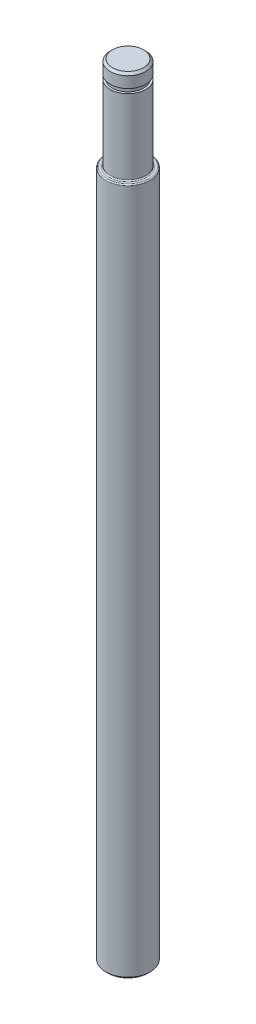
SolidWorks part; units mm, degrees
material "AISI 1045 Aço, trefilado"
ref_plane "Plano frontal" through (0, 0, 0) normal (0, 0, 1) x (1, 0, 0)
ref_plane "Plano superior" through (0, 0, 0) normal (0, 1, 0) x (1, 0, 0)
ref_plane "Plano direito" through (0, 0, 0) normal (1, 0, 0) x (0, 0, -1)
sketch "Esboço1" plane through (0, 0, 0) normal (0, 1, 0) x (1, 0, 0)
  circle A0 centre (0, 0) radius 5
extrude "Ressalto-extrusão1" add sketch "Esboço1" along normal blind 94 and the other way blind 82
sketch "Esboço2" plane through (0, 94, 0) normal (0, 1, 0) x (1, 0, 0)
  circle A0 centre (0, 0) radius 4
  circle A1 centre (0, 0) radius 14
  dimension "D1" = 10
extrude "Corte-extrusão1" cut sketch "Esboço2" against normal blind 21
chamfer "Chanfro1" distance 0.5 1 edges at (0, 94, 4)
fillet "Filete1" radius 0.25 2 edges at (0, 73, 4) (0, 73, 5)
chamfer "Chanfro2" distance 0.5 angle 45 1 edges at (0, -82, 5)
sketch "Esboço3" plane through (0, 94, 0) normal (0, 1, 0) x (1, 0, 0)
  circle A0 centre (0, 0) radius 13.5
  circle A2 centre (0, 0) radius 3.5
  dimension "D1" = 10
extrude "Corte-extrusão2" cut sketch "Esboço3" against normal blind 1 from offset 3
